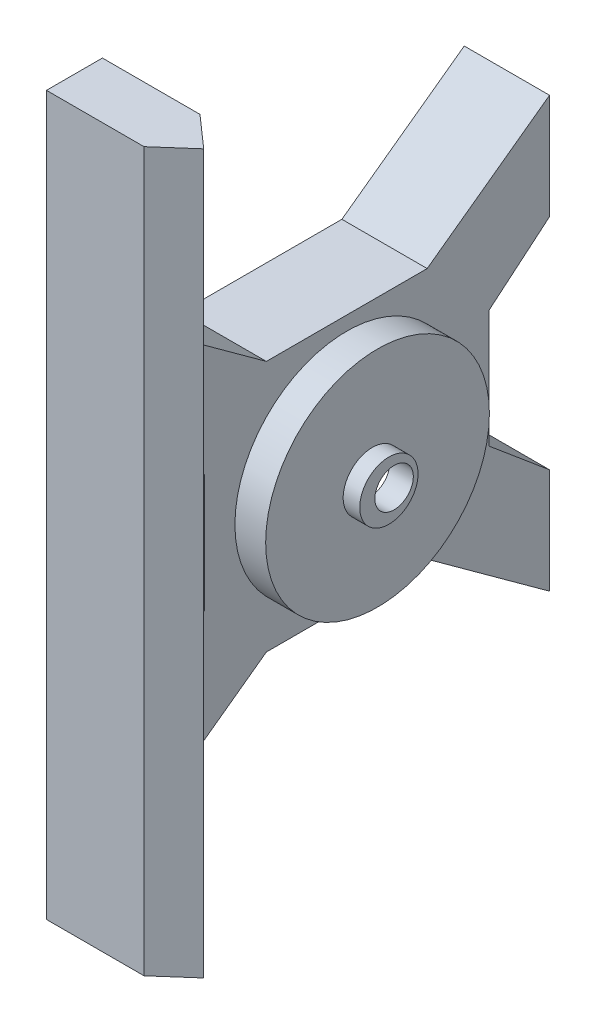
SolidWorks part; units mm, degrees
ref_plane "Front Plane" through (0, 0, 0) normal (0, 0, 1) x (1, 0, 0)
ref_plane "Top Plane" through (0, 0, 0) normal (0, 1, 0) x (1, 0, 0)
ref_plane "Right Plane" through (0, 0, 0) normal (1, 0, 0) x (0, 0, -1)
sketch "Sketch1" plane through (0, 0, 0) normal (1, 0, 0) x (0, 0, -1)
  line L0 (0, 0) -> (0, 1800) construction
  line L1 (0, 0) -> (0, -1304.7337) construction
  line L2 (0, 0) -> (-2305.9172, 0) construction
  line L4 (575, 900) -> (-575, 900)
  line L5 (-575, 900) -> (-1450, 1583.6249) construction
  line L6 (-1450, 1535.7247) -> (-1450, 783.82)
  line L7 (-1450, 758.7631) -> (-1016.5941, 420.1493) construction
  line L8 (-1016.5941, 420.1493) -> (-1016.5941, -420.1493)
  line L9 (0, 0) -> (0, -1800) construction
  line L10 (-1450, -758.7631) -> (-1016.5941, -420.1493) construction
  line L12 (-575, -900) -> (-1450, -1583.6249) construction
  line L13 (575, -900) -> (-575, -900)
  line L14 (-575, 900) -> (-1450, 1535.7247)
  line L15 (-1016.5941, 420.1493) -> (-1450, 783.82)
  line L16 (-1016.5941, -420.1493) -> (-1450, -783.82)
  line L17 (-1450, -1535.7247) -> (-1450, -783.82)
  line L18 (-575, -900) -> (-1450, -1535.7247)
  line L19 (575, -900) -> (1450, -1535.7247)
  line L20 (1450, -1535.7247) -> (1450, -783.82)
  line L21 (1016.5941, -420.1493) -> (1450, -783.82)
  line L22 (1016.5941, 420.1493) -> (1016.5941, -420.1493)
  line L23 (1016.5941, 420.1493) -> (1450, 783.82)
  line L24 (1450, 1535.7247) -> (1450, 783.82)
  line L25 (575, 900) -> (1450, 1535.7247)
  point P13 (-1016.5941, 0)
  point P23 (0, -900)
  point P30 (0, 900)
  dimension "D1" = 1800
  dimension "D2" = 575
  dimension "D3" = 142
  dimension "D4" = 550
  dimension "D5" = 650
  dimension "D6" = 1450
  dimension "D7" = 2
  dimension "D8" = 2
extrude "Boss-Extrude1" add sketch "Sketch1" along normal blind 610
sketch "Sketch4" plane through (0, 900, 0) normal (0, 1, 0) x (1, 0, 0)
  line L0 (0, 1450) -> (0, -1450)
  line L1 (0, -1450) -> (362.8031, -1450)
  line L2 (610, -1450) -> (0, -1450) construction
  line L3 (362.8031, -1450) -> (610, -105.9724)
  line L4 (610, 575) -> (610, -575) construction
  line L5 (610, -105.9724) -> (400, 1450)
  line L6 (610, 1450) -> (0, 1450) construction
  line L7 (400, 1450) -> (0, 1450)
  circle A0 centre (610, -105.9724) radius 1977.2282
  dimension "D1" = 400
sketch "Sketch5" plane through (0, 0, 0) normal (1, 0, 0) x (0, 0, -1)
  circle A0 centre (0, 0) radius 800
  dimension "D1" = 1600
extrude "Boss-Extrude2" add sketch "Sketch5" along normal blind 830
shell "Shell1" thickness 50
sketch "Sketch6" plane through (830, 0, 0) normal (1, 0, 0) x (0, 0, -1)
  circle A0 centre (0, 0) radius 137.5
  dimension "D1" = 275
extrude "Cut-Extrude6" cut sketch "Sketch6" against normal blind 830 contours A0
sketch "Sketch7" plane through (830, 0, 0) normal (1, 0, 0) x (0, 0, -1)
  circle A0 centre (0, 0) radius 137.5 construction
  circle A1 centre (0, 0) radius 137.5
  circle A2 centre (-37.2797, 0) radius 208.5
  dimension "D1" = 417
extrude "Boss-Extrude3" add sketch "Sketch7" along normal blind 118.5
sketch "Sketch8" plane through (0, 0, 0) normal (0, 1, 0) x (1, 0, 0)
  line L0 (399.5876, -1250) -> (-274.0277, -1250) construction
  line L1 (837.2336, -1250) -> (610, -1450)
  line L2 (610, -1450) -> (-87.5, -1450)
  line L3 (-87.5, -1450) -> (-87.5, -1050)
  line L4 (610, -1050) -> (-87.5, -1050)
  line L5 (837.2336, -1250) -> (610, -1050)
  line L6 (0, 1450) -> (0, -1450) construction
  line L7 (362.8031, -1450) -> (610, -105.9724) construction
  line L8 (610, -1450) -> (610, -575) construction
  point P7 (-87.5, -1250)
  dimension "D5" = 1250
  dimension "D6" = 87.5
extrude "Boss-Extrude5" add sketch "Sketch8" along normal blind 2667.5 and the other way blind 2467.5
